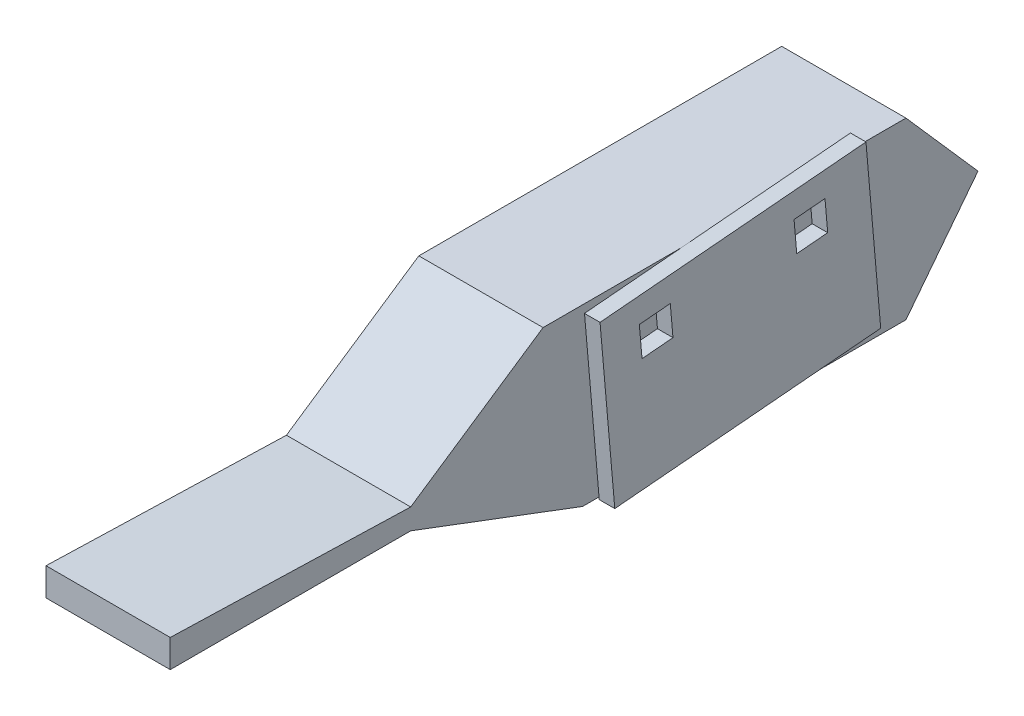
SolidWorks part; units mm, degrees
ref_plane "Front Plane" through (0, 0, 0) normal (0, 0, 1) x (1, 0, 0)
ref_plane "Top Plane" through (0, 0, 0) normal (0, 1, 0) x (1, 0, 0)
ref_plane "Right Plane" through (0, 0, 0) normal (1, 0, 0) x (0, 0, -1)
sketch "Sketch1" plane through (0, 0, 0) normal (1, 0, 0) x (0, 0, -1)
  line L0 (-68.2973, 0) -> (-41.2361, 18.2249)
  line L1 (-41.2361, 18.2249) -> (32.9521, 18.2249)
  line L2 (32.9521, 18.2249) -> (47.6792, 1.4727)
  line L3 (47.6792, 1.4727) -> (32.9521, -17.4885)
  line L4 (32.9521, -17.4885) -> (-33.1361, -17.4885)
  line L5 (-33.1361, -17.4885) -> (-68.2973, -4.2341)
  line L6 (-68.2973, -4.2341) -> (-117.4492, -4.2341)
  line L7 (-117.4492, -4.2341) -> (-117.4492, 1.4727)
  line L8 (-117.4492, 1.4727) -> (-68.2973, 0)
extrude "Boss-Extrude1" add sketch "Sketch1" along normal mid plane 25.4
sketch "Sketch2" plane through (12.7, 0, 0) normal (1, 0, 0) x (0, 0, -1)
  line L1 (-29.7472, -17.9853) -> (24.6176, -13.229)
  line L2 (-29.7472, -17.9853) -> (-32.7646, 16.504)
  line L3 (-32.7646, 16.504) -> (21.6002, 21.2603)
  line L4 (24.6176, -13.229) -> (21.6002, 21.2603)
  line L7 (-24.1774, 5.7816) -> (-17.8516, 6.3351)
  line L8 (-24.1774, 5.7816) -> (-24.7308, 12.1075)
  line L9 (-24.7308, 12.1075) -> (-18.405, 12.6609)
  line L10 (-17.8516, 6.3351) -> (-18.405, 12.6609)
  line L11 (7.4518, 8.5488) -> (13.7776, 9.1023)
  line L12 (7.4518, 8.5488) -> (6.8983, 14.8747)
  line L13 (6.8983, 14.8747) -> (13.2242, 15.4281)
  line L14 (13.7776, 9.1023) -> (13.2242, 15.4281)
  line L15 (-33.1361, -17.4885) -> (32.9521, -17.4885) construction
  line L16 (-17.8516, 6.3351) -> (6.8983, 14.8747) construction
  line L17 (32.9521, 18.2249) -> (-41.2361, 18.2249) construction
  point P16 (-5.4766, 10.6049)
  dimension "D1" = 6.35
  dimension "D2" = 6.35
  dimension "D3" = 6.35
  dimension "D4" = 6.35
  dimension "D5" = 5.08
  dimension "D6" = 25.4
  dimension "D7" = 7.62
  dimension "D8" = 5
  dimension "D9" = 7.62
extrude "Boss-Extrude2" add sketch "Sketch2" along normal blind 3.175
equation "\"D3@Sketch2\"=\"D1@Sketch2\""
equation "\"D4@Sketch2\"=\"D1@Sketch2\""
equation "\"D2@Sketch2\"=\"D1@Sketch2\""
